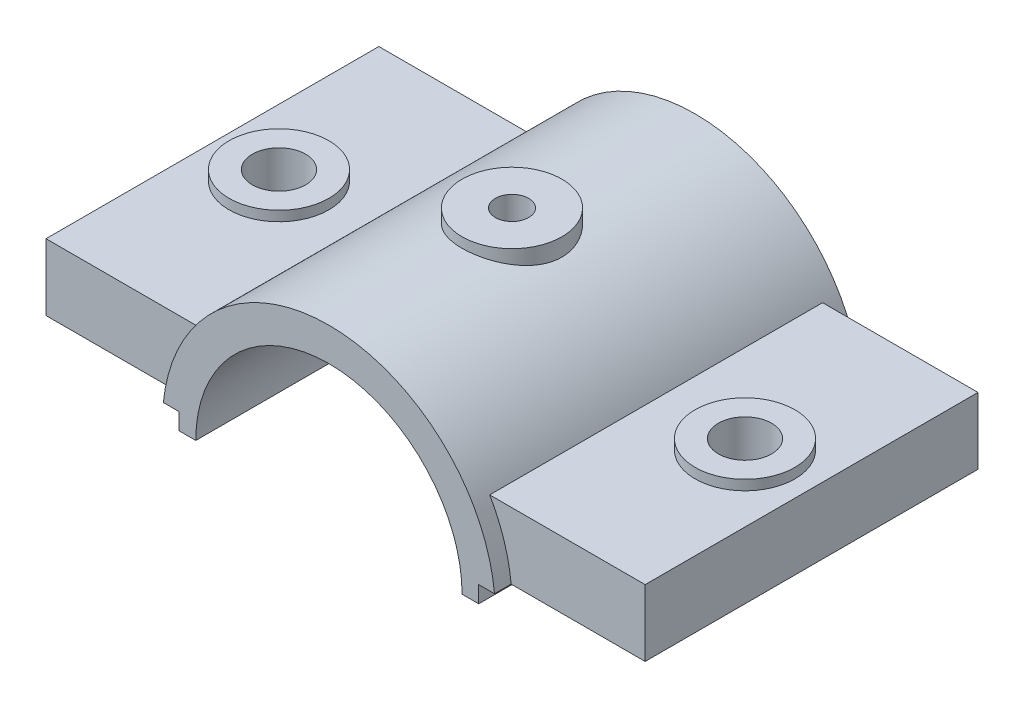
SolidWorks part; units mm, degrees
ref_plane "Front Plane" through (0, 0, 0) normal (0, 0, 1) x (1, 0, 0)
ref_plane "Top Plane" through (0, 0, 0) normal (0, 1, 0) x (1, 0, 0)
ref_plane "Right Plane" through (0, 0, 0) normal (1, 0, 0) x (0, 0, -1)
sketch "Sketch2" plane through (0, 0, 0) normal (0, 0, 1) x (1, 0, 0)
  line L0 (-50, 0) -> (50, 0)
  arc A0 (-50, 0) -> (50, 0) centre (0, 0) cw
  dimension "D1" = 50
extrude "Boss-Extrude1" add sketch "Sketch2" along normal mid plane 110
sketch "Sketch4" plane through (0, 0, 0) normal (0, 0, 1) x (1, 0, 0)
  line L0 (0, 0) -> (0, -8.942) construction
  line L1 (-90, 5) -> (90, 5)
  line L2 (-90, 5) -> (-90, 25)
  line L3 (-90, 25) -> (90, 25)
  line L4 (90, 5) -> (90, 25)
  line L5 (-50, 0) -> (50, 0) construction
  dimension "D1" = 5
  dimension "D2" = 180
  dimension "D3" = 20
extrude "Boss-Extrude2" add sketch "Sketch4" along normal mid plane 100
sketch "Sketch5" plane through (0, 0, 55) normal (0, 0, 1) x (1, 0, 0)
  line L0 (90, 5) -> (90, 25) construction
  line L1 (45, 0) -> (90, 0)
  line L2 (45, 0) -> (45, 5)
  line L3 (45, 5) -> (90, 5)
  line L4 (90, 0) -> (90, 5)
  line L5 (-90, 5) -> (-49.7494, 5) construction
  line L6 (-50, 0) -> (50, 0) construction
  dimension "D1" = 5
extrude "Cut-Extrude1" cut sketch "Sketch5" against normal up to next
mirror "Mirror1" about plane through (0, 0, 0) normal (1, 0, 0) of "Cut-Extrude1"
sketch "Sketch6" plane through (0, 0, 55) normal (0, 0, 1) x (1, 0, 0)
  line L0 (-45, 0) -> (45, 0) construction
  line L1 (-40, 0) -> (40, 0)
  arc A0 (-40, 0) -> (40, 0) centre (0, 0) cw
  dimension "D1" = 40
extrude "Cut-Extrude2" cut sketch "Sketch6" against normal up to next
sketch "Sketch7" plane through (0, 25, 0) normal (0, 1, 0) x (1, 0, 0)
  circle A0 centre (70, 0) radius 15
  dimension "D1" = 30
  dimension "D2" = 70
extrude "Boss-Extrude3" add sketch "Sketch7" along normal blind 3
mirror "Mirror2" about plane through (0, 0, 0) normal (1, 0, 0) of "Boss-Extrude3"
hole_wizard "Hole1" positions "Sketch8" profile "Sketch9" legacy end condition up to next
sketch "Sketch8" plane through (0, 28, 0) normal (0, 1, 0) x (1, 0, 0)
  point P0 (70, 0)
  point P4 (-70, 0)
sketch "Sketch9" plane through (70, 28, 0) normal (1, 0, 0) x (0, 0, 1)
  line L0 (0, 0) -> (0, 23)
  line L1 (0, 23) -> (8, 23)
  line L2 (8, 23) -> (8, 0)
  line L3 (8, 0) -> (0, 0)
  line L4 (0, 110) -> (0, -10) construction
  dimension "Diameter" = 16
  dimension "Depth" = 23
ref_plane "Plane1" through (0, 53, 0) normal (0, 1, 0) x (1, 0, 0)
sketch "Sketch10" plane through (0, 53, 0) normal (0, 1, 0) x (1, 0, 0)
  circle A0 centre (0, 0) radius 15
  dimension "D1" = 30
extrude "Boss-Extrude4" add sketch "Sketch10" against normal up to next
hole_wizard "Hole2" positions "Sketch11" profile "Sketch12" legacy end condition up to next
sketch "Sketch11" plane through (0, 53, 0) normal (0, 1, 0) x (1, 0, 0)
  point P0 (0, 0)
sketch "Sketch12" plane through (0, 53, 0) normal (1, 0, 0) x (0, 0, 1)
  line L0 (0, 0) -> (0, 13)
  line L1 (0, 13) -> (5, 13)
  line L2 (5, 13) -> (5, 0)
  line L3 (5, 0) -> (0, 0)
  line L4 (0, 110) -> (0, -10) construction
  dimension "Diameter" = 10
  dimension "Depth" = 13
sketch "Sketch13" plane through (0, 0, 0) normal (0, 1, 0) x (1, 0, 0)
  circle A0 centre (0, 0) radius 8
  dimension "D1" = 16
extrude "Cut-Extrude3" cut sketch "Sketch13" along normal blind 42
